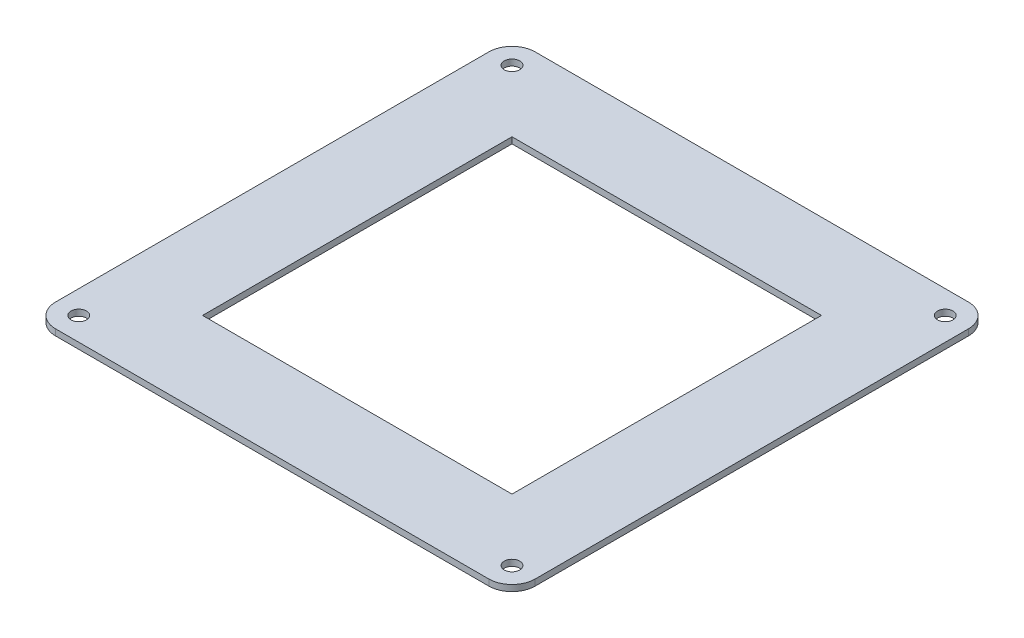
SolidWorks part; units mm, degrees
ref_plane "Alzado" through (0, 0, 0) normal (0, 0, 1) x (1, 0, 0)
ref_plane "Planta" through (0, 0, 0) normal (0, 1, 0) x (1, 0, 0)
ref_plane "Vista lateral" through (0, 0, 0) normal (1, 0, 0) x (0, 0, -1)
sketch "Croquis1" plane through (0, 0, 0) normal (0, 1, 0) x (1, 0, 0)
  line L0 (87.5, 17.5) -> (87.5, 10) construction
  line L1 (17.5, 10) -> (157.5, 10)
  line L2 (10, 17.5) -> (10, 157.5)
  line L3 (17.5, 165) -> (157.5, 165)
  line L4 (165, 17.5) -> (165, 157.5)
  line L5 (17.5, 17.5) -> (157.5, 17.5) construction
  line L6 (17.5, 17.5) -> (17.5, 157.5) construction
  line L7 (17.5, 157.5) -> (157.5, 157.5) construction
  line L8 (157.5, 17.5) -> (157.5, 157.5) construction
  line L9 (157.5, 87.5) -> (165, 87.5) construction
  line L10 (17.5, 157.5) -> (157.5, 17.5) construction
  line L12 (87.5, 87.5) -> (157.5, 157.5) construction
  circle A0 centre (17.5, 157.5) radius 2.5
  circle A1 centre (157.5, 157.5) radius 2.5
  circle A2 centre (157.5, 17.5) radius 2.5
  circle A3 centre (17.5, 17.5) radius 2.5
  arc A4 (17.5, 165) -> (10, 157.5) centre (17.5, 157.5) ccw
  arc A5 (165, 157.5) -> (157.5, 165) centre (157.5, 157.5) ccw
  arc A6 (157.5, 10) -> (165, 17.5) centre (157.5, 17.5) ccw
  arc A7 (10, 17.5) -> (17.5, 10) centre (17.5, 17.5) ccw
  dimension "D3" = 5
  dimension "D1" = 15
  dimension "D2" = 140
  dimension "D4" = 4
extrude "Saliente-Extruir1" add sketch "Croquis1" along normal blind 2
sketch "Croquis2" plane through (0, 2, 0) normal (0, 1, 0) x (1, 0, 0)
  line L0 (10, 87.5) -> (165, 87.5) construction
  line L1 (10, 157.5) -> (10, 17.5) construction
  line L2 (165, 17.5) -> (165, 157.5) construction
  line L3 (87.5, 10) -> (87.5, 165) construction
  line L4 (17.5, 10) -> (157.5, 10) construction
  line L5 (157.5, 165) -> (17.5, 165) construction
  line L7 (37.5, 37.5) -> (137.5, 37.5)
  line L8 (37.5, 37.5) -> (37.5, 137.5)
  line L9 (37.5, 137.5) -> (137.5, 137.5)
  line L10 (137.5, 37.5) -> (137.5, 137.5)
  line L11 (37.5, 37.5) -> (137.5, 137.5) construction
  line L12 (37.5, 137.5) -> (137.5, 37.5) construction
  point P12 (87.5, 87.5)
  dimension "D1" = 100
extrude "Cortar-Extruir1" cut sketch "Croquis2" against normal blind 10
